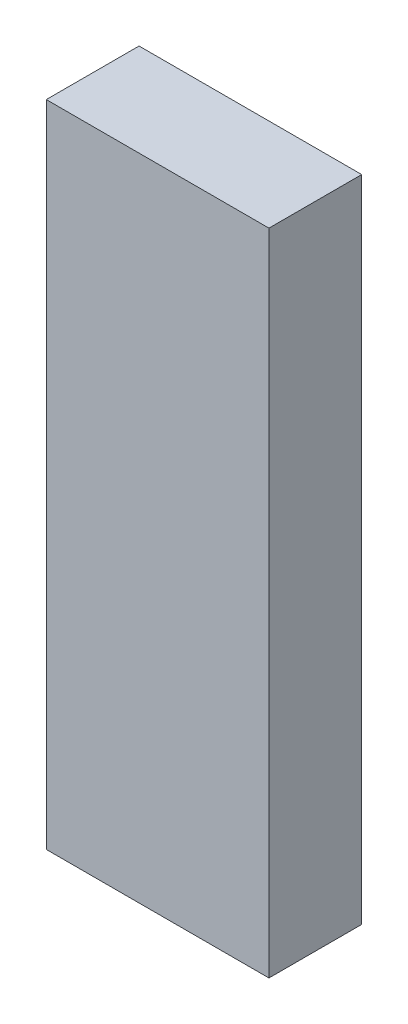
SolidWorks part; units mm, degrees
ref_plane "Front Plane" through (0, 0, 0) normal (0, 0, 1) x (1, 0, 0)
ref_plane "Top Plane" through (0, 0, 0) normal (0, 1, 0) x (1, 0, 0)
ref_plane "Right Plane" through (0, 0, 0) normal (1, 0, 0) x (0, 0, -1)
sketch "Sketch1" plane through (0, 0, 0) normal (0, 0, 1) x (1, 0, 0)
  line L1 (-6, 17.5) -> (6, 17.5)
  line L2 (-6, 17.5) -> (-6, -17.5)
  line L3 (-6, -17.5) -> (6, -17.5)
  line L4 (6, 17.5) -> (6, -17.5)
  dimension "D1" = 12
  dimension "D2" = 35
  dimension "D3" = 6
  dimension "D4" = 17.5
extrude "Boss-Extrude1" add sketch "Sketch1" along normal blind 5
